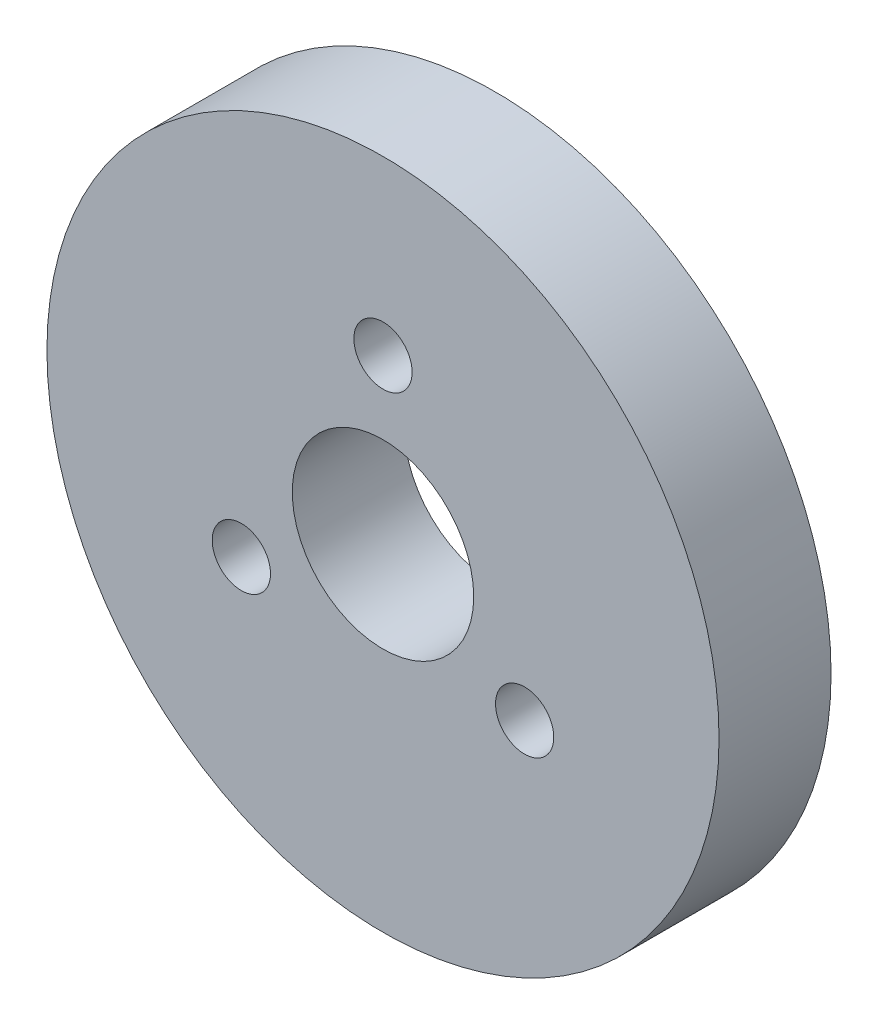
SolidWorks part; units mm, degrees
ref_plane "Front Plane" through (0, 0, 0) normal (0, 0, 1) x (1, 0, 0)
ref_plane "Top Plane" through (0, 0, 0) normal (0, 1, 0) x (1, 0, 0)
ref_plane "Right Plane" through (0, 0, 0) normal (1, 0, 0) x (0, 0, -1)
sketch "Sketch1" plane through (0, 0, 0) normal (0, 0, 1) x (1, 0, 0)
  line L0 (0, 0) -> (0, 9.4773) construction
  circle A0 centre (0, 0) radius 4.05
  circle A1 centre (0, 0) radius 15
  circle A2 centre (0, 7.3) radius 3.25 construction
  circle A3 centre (0, 7.3) radius 1.3
  circle A4 centre (6.322, -3.65) radius 1.3
  circle A5 centre (-6.322, -3.65) radius 1.3
  point P14 (0, 0)
  dimension "D1" = 8.1
  dimension "D2" = 30
  dimension "D3" = 6.5
  dimension "D4" = 2.6
  dimension "D5" = 3
extrude "Boss-Extrude1" add sketch "Sketch1" along normal blind 5
